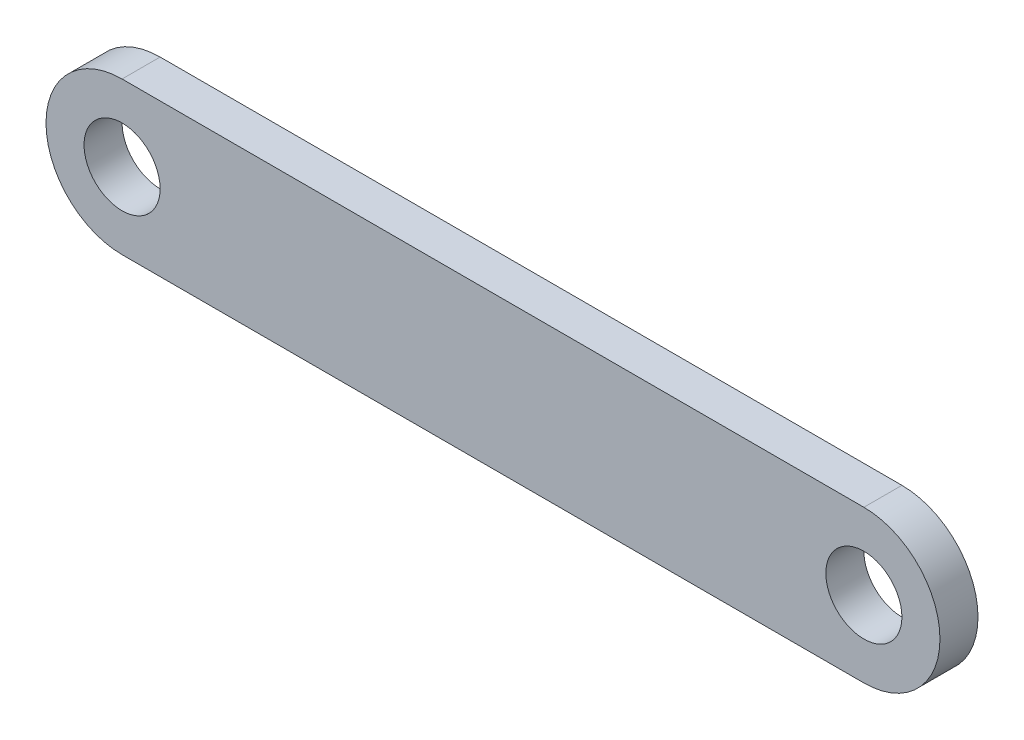
SolidWorks part; units mm, degrees
ref_plane "Plano frontal" through (0, 0, 0) normal (0, 0, 1) x (1, 0, 0)
ref_plane "Plano superior" through (0, 0, 0) normal (0, 1, 0) x (1, 0, 0)
ref_plane "Plano direito" through (0, 0, 0) normal (1, 0, 0) x (0, 0, -1)
sketch "Esboço1" plane through (0, 0, 0) normal (0, 0, 1) x (1, 0, 0)
  line L0 (-9.75, 2) -> (9.75, 2)
  line L1 (-9.75, 0) -> (9.75, 0) construction
  line L2 (-9.75, -2) -> (9.75, -2)
  arc A0 (-9.75, 2) -> (-9.75, -2) centre (-9.75, 0) ccw
  arc A1 (9.75, 2) -> (9.75, -2) centre (9.75, 0) cw
  circle A2 centre (-9.75, 0) radius 1
  circle A3 centre (9.75, 0) radius 1
  point P3 (0, 2)
  dimension "D1" = 19.5
  dimension "D2" = 2
extrude "Ressalto-extrusão1" add sketch "Esboço1" along normal blind 1
